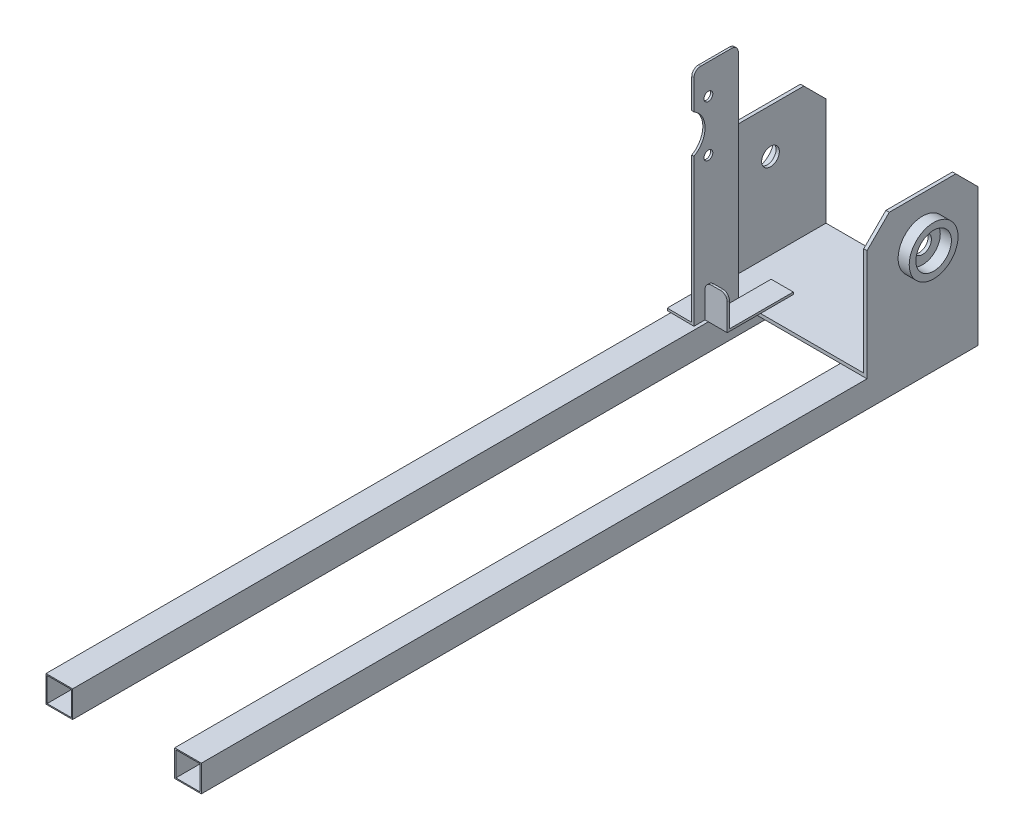
SolidWorks part; units mm, degrees
ref_plane "Front Plane" through (0, 0, 0) normal (0, 0, 1) x (1, 0, 0)
ref_plane "Top Plane" through (0, 0, 0) normal (0, 1, 0) x (1, 0, 0)
ref_plane "Right Plane" through (0, 0, 0) normal (1, 0, 0) x (0, 0, -1)
sketch "Sketch1" plane through (0, 0, 0) normal (0, 0, 1) x (1, 0, 0)
  line L0 (-65.8165, 13.0444) -> (-65.8165, -46.9556)
  line L1 (-65.8165, -46.9556) -> (4.1835, -46.9556)
  line L2 (4.1835, -46.9556) -> (4.1835, 13.0444)
  line L3 (-64.3165, 13.0444) -> (-64.3165, -45.4556)
  line L4 (-64.3165, -45.4556) -> (2.6835, -45.4556)
  line L5 (2.6835, -45.4556) -> (2.6835, 13.0444)
  line L6 (-65.8165, 13.0444) -> (-64.3165, 13.0444)
  line L8 (2.6835, 13.0444) -> (4.1835, 13.0444)
  dimension "D1" = 60
  dimension "D2" = 60
  dimension "D3" = 70
  dimension "D4" = 1.5
extrude "Boss-Extrude1" add sketch "Sketch1" along normal blind 50 contours L0 L1 L2 L8 L5 L4 L3 L6
chamfer "Chamfer1" distance 10 angle 45 4 edges at (-65.0665, 13.0444, 0) (-65.0665, 13.0444, 50) (3.4335, 13.0444, 50) (3.4335, 13.0444, 0)
sketch "Sketch2" plane through (4.1835, 0, 0) normal (1, 0, 0) x (0, 0, -1)
  line L2 (-40, 13.0444) -> (-10, 13.0444) construction
  circle A0 centre (-25, -6.9556) radius 4
  dimension "D1" = 20
  dimension "D2" = 8
extrude "Cut-Extrude1" cut sketch "Sketch2" against normal blind 80
sketch "Sketch3" plane through (4.1835, 0, 0) normal (1, 0, 0) x (0, 0, -1)
  circle A0 centre (-25, -6.9556) radius 11
  circle A1 centre (-25, -6.9556) radius 8
  dimension "D1" = 22
  dimension "D2" = 16
extrude "Boss-Extrude2" add sketch "Sketch3" along normal blind 5 contours A0 | A1
ref_plane "Plane1" through (-30.8165, 0, 0) normal (-1, 0, 0) x (0, 0, 1)
mirror "Mirror1" about plane through (-30.8165, 0, 0) normal (-1, 0, 0) of "Boss-Extrude2"
sketch "Sketch4" plane through (0, 0, 0) normal (0, 0, -1) x (-1, 0, 0)
  line L0 (-4.1835, -46.9556) -> (7.8165, -46.9556)
  line L1 (65.8165, -46.9556) -> (-4.1835, -46.9556) construction
  line L2 (7.8165, -46.9556) -> (7.8165, -58.9556)
  line L3 (7.8165, -58.9556) -> (-4.1835, -58.9556)
  line L4 (-4.1835, -58.9556) -> (-4.1835, -46.9556)
  dimension "D1" = 12
  dimension "D2" = 12
extrude "Boss-Extrude3" add sketch "Sketch4" against normal blind 350
mirror "Mirror2" about plane through (-30.8165, 0, 0) normal (-1, 0, 0) of "Boss-Extrude3"
sketch "Sketch5" plane through (0, 0, 0) normal (0, 0, -1) x (-1, 0, 0)
  line L1 (7.8165, -58.9556) -> (53.8165, -58.9556)
  line L2 (7.8165, -58.9556) -> (7.8165, -46.9556)
  line L3 (7.8165, -46.9556) -> (53.8165, -46.9556)
  line L4 (53.8165, -58.9556) -> (53.8165, -46.9556)
extrude "Boss-Extrude4" add sketch "Sketch5" against normal blind 12
sketch "Sketch9" plane through (0, 0, 350) normal (0, 0, 1) x (1, 0, 0)
  line L0 (-65.3165, -47.4556) -> (-65.3165, -58.4556)
  line L5 (-65.3165, -58.4556) -> (-54.3165, -58.4556)
  line L6 (-54.3165, -47.4556) -> (-54.3165, -58.4556)
  line L7 (-65.3165, -47.4556) -> (-54.3165, -47.4556)
extrude "Cut-Extrude3" cut sketch "Sketch9" against normal blind 380
mirror "Mirror3" about plane through (-30.8165, 0, 0) normal (-1, 0, 0) of "Cut-Extrude3"
sketch "Sketch10" plane through (-53.8165, 0, 0) normal (1, 0, 0) x (0, 0, -1)
  line L0 (-35.2375, -45.4556) -> (-65, -45.4556)
  line L1 (-65, -45.4556) -> (-65, -30.4556)
  line L2 (-50, -46.9556) -> (-50, 3.0444) construction
  line L3 (-35.2375, -44.4556) -> (-64, -44.4556)
  line L4 (-64, -44.4556) -> (-64, -30.4556)
  line L5 (-65, -30.4556) -> (-64, -30.4556)
  line L6 (-35.2375, -44.4556) -> (-35.2375, -45.4556)
  dimension "D1" = 15
  dimension "D2" = 29.7625
  dimension "D3" = 15
  dimension "D4" = 1
extrude "Boss-Extrude5" add sketch "Sketch10" along normal blind 10
fillet "Fillet1" radius 3 2 edges at (-53.8165, -30.4556, 64.5) (-43.8165, -30.4556, 64.5)
sketch "Sketch11" plane through (0, 0, 50) normal (0, 0, 1) x (1, 0, 0)
  line L0 (-65.8165, -45.3459) -> (-53.8165, -45.4556)
  line L1 (-53.8165, -45.4556) -> (-53.8165, 54.5444)
  line L2 (-65.8407, -44.3456) -> (-54.8165, -44.4465)
  line L3 (-54.8165, -44.4465) -> (-54.8165, 54.5444)
  line L4 (-65.8407, -44.3456) -> (-65.8165, -45.3459)
  line L5 (-65.8165, 3.0444) -> (-65.8165, -46.9556) construction
  line L6 (-67.159, -44.3336) -> (-54.8165, -44.4465) construction
  line L7 (-67.1681, -45.3336) -> (-53.8165, -45.4556) construction
  line L8 (-54.8165, 54.5444) -> (-53.8165, 54.5444)
  dimension "D1" = 100
  dimension "D2" = 1
extrude "Boss-Extrude6" add sketch "Sketch11" along normal blind 20
fillet "Fillet2" radius 3 2 edges at (-54.3165, 54.5444, 70) (-54.3165, 54.5444, 50)
sketch "Sketch12" plane through (-53.8165, 0, 0) normal (1, 0, 0) x (0, 0, -1)
  line L0 (-70, -45.4556) -> (-70, 51.5444) construction
  line L2 (-65.5, 18.0444) -> (-63.5, 18.0444)
  line L5 (-65.5, 41.0444) -> (-63.5, 41.0444)
  line L7 (-82.0711, 22.4733) -> (-63.5, 41.0444) construction
  line L8 (-82.0711, 36.6154) -> (-63.5, 18.0444) construction
  circle A0 centre (-75, 29.5444) radius 10
  circle A1 centre (-63.5, 41.0444) radius 2
  circle A2 centre (-63.5, 18.0444) radius 2
  dimension "D4" = 75
  dimension "D2" = 23
  dimension "D3" = 5
extrude "Cut-Extrude5" cut sketch "Sketch12" against normal blind 10
sketch "Sketch13" plane through (-30.8165, 0, 0) normal (-1, 0, 0) x (0, 0, 1)
  circle A0 centre (25, -6.9556) radius 4
